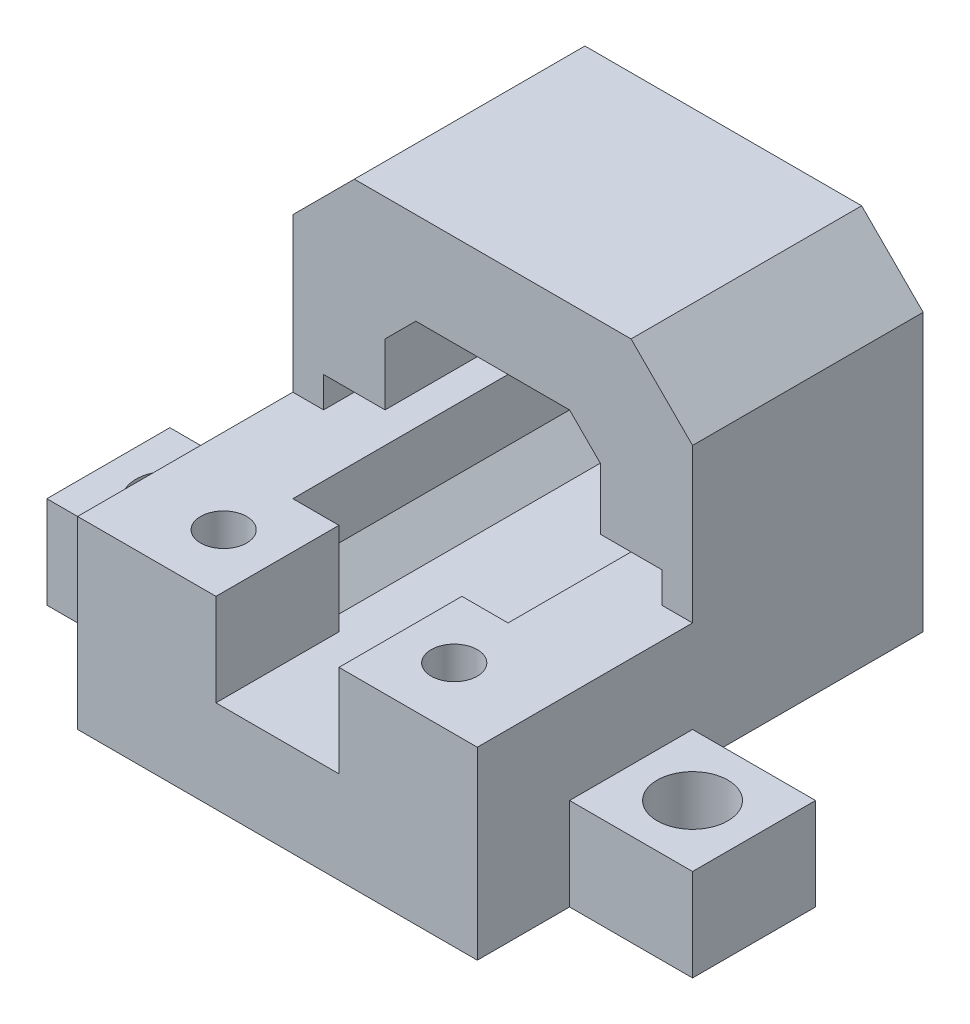
SolidWorks part; units mm, degrees
ref_plane "Plan de face" through (0, 0, 0) normal (0, 0, 1) x (1, 0, 0)
ref_plane "Plan de dessus" through (0, 0, 0) normal (0, 1, 0) x (1, 0, 0)
ref_plane "Plan de droite" through (0, 0, 0) normal (1, 0, 0) x (0, 0, -1)
sketch "Esquisse1" plane through (0, 0, 0) normal (0, 0, 1) x (1, 0, 0)
  line L0 (-7, 0) -> (7, 0) construction
  line L1 (7, 0) -> (13, 0) construction
  line L2 (7, 0) -> (7, -5)
  line L3 (7, -5) -> (7, -7) construction
  line L4 (7, -7) -> (5, -7) construction
  line L5 (7, -5) -> (5, -7)
  line L6 (5, -7) -> (-5, -7)
  line L7 (13, 0) -> (13, -9)
  line L8 (13, -9) -> (13, -13) construction
  line L9 (13, -13) -> (9, -13) construction
  line L10 (9, -13) -> (13, -9)
  line L11 (0, 0) -> (0, -7) construction
  line L12 (7, -5) -> (13, -9) construction
  line L13 (13, 0) -> (13, 9)
  line L14 (7, 0) -> (7, 5)
  line L15 (7, 5) -> (7, 7) construction
  line L16 (7, 7) -> (5, 7) construction
  line L17 (7, 5) -> (5, 7)
  line L18 (5, 7) -> (-5, 7)
  line L19 (0, 7) -> (0, 0) construction
  line L20 (13, 9) -> (13, 13) construction
  line L21 (13, 13) -> (9, 13) construction
  line L22 (9, 13) -> (13, 9)
  line L23 (9, 13) -> (0, 13)
  line L24 (0, 13) -> (0, 7) construction
  line L25 (9, -13) -> (-9, -13)
  line L26 (0, -13) -> (0, -7) construction
  line L27 (-13, 13) -> (-9, 13) construction
  line L28 (-13, 9) -> (-13, 13) construction
  line L29 (-7, 7) -> (-5, 7) construction
  line L30 (-7, 5) -> (-7, 7) construction
  line L31 (-13, -13) -> (-9, -13) construction
  line L32 (-13, -9) -> (-13, -13) construction
  line L33 (-7, -7) -> (-5, -7) construction
  line L34 (-7, -5) -> (-7, -7) construction
  line L35 (-7, 0) -> (-13, 0) construction
  line L36 (-9, 13) -> (0, 13)
  line L37 (-9, 13) -> (-13, 9)
  line L38 (-7, 5) -> (-5, 7)
  line L39 (-7, 0) -> (-7, 5)
  line L40 (-13, 0) -> (-13, 9)
  line L41 (-7, -5) -> (-13, -9) construction
  line L42 (-9, -13) -> (-13, -9)
  line L43 (-13, 0) -> (-13, -9)
  line L44 (-7, -5) -> (-5, -7)
  line L45 (-7, 0) -> (-7, -5)
  point P36 (0, 12.572)
  dimension "D1" = 7
  dimension "D2" = 5
  dimension "D3" = 2
  dimension "D4" = 6
  dimension "D5" = 13
  dimension "D6" = 9
  dimension "D7" = 7
  dimension "D8" = 4
  dimension "D9" = 5
  dimension "D10" = 2
  dimension "D11" = 2
  dimension "D12" = 26
  dimension "D14" = 18
  dimension "D16" = 10
  dimension "D17" = 14
extrude "Boss.-Extru.1" add sketch "Esquisse1" along normal blind 15
sketch "Esquisse2" plane through (0, 0, 15) normal (0, 0, 1) x (1, 0, 0)
  line L0 (-9, -13) -> (9, -13)
  line L1 (9, -13) -> (13, -9)
  line L7 (7, -5) -> (5, -7)
  line L8 (5, -7) -> (-5, -7)
  line L9 (-5, -7) -> (-7, -5)
  line L15 (-13, -9) -> (-9, -13)
  line L16 (-7, -5) -> (-7, -1)
  line L17 (-7, 5) -> (-7, -5) construction
  line L18 (-13, -9) -> (-13, -1)
  line L19 (-13, 9) -> (-13, -9) construction
  line L20 (-13, -1) -> (-7, -1)
  line L21 (7, -5) -> (7, -1)
  line L22 (7, -5) -> (7, 5) construction
  line L23 (7, -1) -> (13, -1)
  line L24 (13, -9) -> (13, 9) construction
  line L25 (13, -1) -> (13, -9)
extrude "Boss.-Extru.2" add sketch "Esquisse2" along normal blind 14
sketch "Esquisse3" plane through (0, 0, 15) normal (0, 0, 1) x (1, 0, 0)
  line L13 (-7, -1) -> (-11, -1)
  line L15 (-7, -1) -> (-13, -1) construction
  line L16 (-11, -1) -> (-11, 1)
  line L17 (-11, 1) -> (-7, 1)
  line L18 (-7, 5) -> (-7, -1) construction
  line L19 (-7, 1) -> (-7, -1)
  line L20 (7, -1) -> (7, 1)
  line L21 (7, -1) -> (7, 5) construction
  line L22 (7, 1) -> (11, 1)
  line L23 (11, 1) -> (11, -1)
  line L24 (13, -1) -> (7, -1) construction
  line L25 (11, -1) -> (7, -1)
extrude "Enlèv. mat.-Extru.1" cut sketch "Esquisse3" against normal blind 10
sketch "Esquisse5" plane through (0, 0, 29) normal (0, 0, 1) x (1, 0, 0)
  line L1 (-4, -1) -> (-7, -1)
  line L2 (-7, -1) -> (-7, -5)
  line L3 (-7, -5) -> (-5, -7)
  line L4 (-5, -7) -> (-4, -7)
  line L5 (5, -7) -> (-5, -7) construction
  line L6 (-4, -7) -> (-4, -1)
  line L7 (5, -7) -> (7, -5)
  line L8 (7, -5) -> (7, -1)
  line L9 (7, -1) -> (4, -1)
  line L10 (4, -1) -> (4, -7)
  line L11 (4, -7) -> (5, -7)
extrude "Boss.-Extru.3" add sketch "Esquisse5" against normal blind 8
sketch "Esquisse6" plane through (0, -1, 0) normal (0, 1, 0) x (1, 0, 0)
  line L0 (-7, -15) -> (-7, -25) construction
  line L1 (-7, -21) -> (-7, -5) construction
  line L2 (9, -15) -> (-9, -15) construction
  line L3 (0, -55) -> (0, 55) construction
  line L4 (7, -15) -> (7, -25) construction
  line L5 (-7, -25) -> (-7.5, -25) construction
  line L6 (7, -25) -> (7.5, -25) construction
  line L7 (-7.5, -25) -> (7.5, -25) construction
  circle A2 centre (-7.5, -25) radius 1.5
  circle A3 centre (7.5, -25) radius 1.5
  dimension "D1" = 15
extrude "Enlèv. mat.-Extru.2" cut sketch "Esquisse6" against normal blind 10
sketch "Esquisse8" plane through (0, 0, 29) normal (0, 0, 1) x (1, 0, 0)
  line L0 (-13, -9) -> (-9, -13)
  line L1 (-9, -13) -> (-13, -13)
  line L2 (-13, -13) -> (-13, -9)
  line L3 (9, -13) -> (13, -13)
  line L4 (13, -13) -> (13, -9)
  line L5 (13, -9) -> (9, -13)
extrude "Boss.-Extru.4" add sketch "Esquisse8" against normal blind 14 contours L4 L5 L3 | L2 L0 L1
sketch "Esquisse9" plane through (0, -13, 0) normal (0, -1, 0) x (1, 0, 0)
  line L0 (-13, 15) -> (-13, 23)
  line L1 (-13, 15) -> (-13, 29) construction
  line L2 (-13, 23) -> (-21, 23)
  line L3 (-21, 23) -> (-21, 15)
  line L4 (-21, 15) -> (-13, 15)
  line L5 (-21, 23) -> (-13, 15) construction
  line L6 (-21, 15) -> (-13, 23) construction
  line L7 (13, 15) -> (21, 15)
  line L8 (21, 15) -> (21, 23)
  line L9 (21, 23) -> (13, 23)
  line L10 (13, 15) -> (13, 29) construction
  line L11 (13, 23) -> (13, 15)
  line L12 (21, 23) -> (13, 15) construction
  line L13 (13, 23) -> (21, 15) construction
  circle A0 centre (-17, 19) radius 2.2
  circle A1 centre (17, 19) radius 2.3
extrude "Boss.-Extru.5" add sketch "Esquisse9" against normal blind 6
